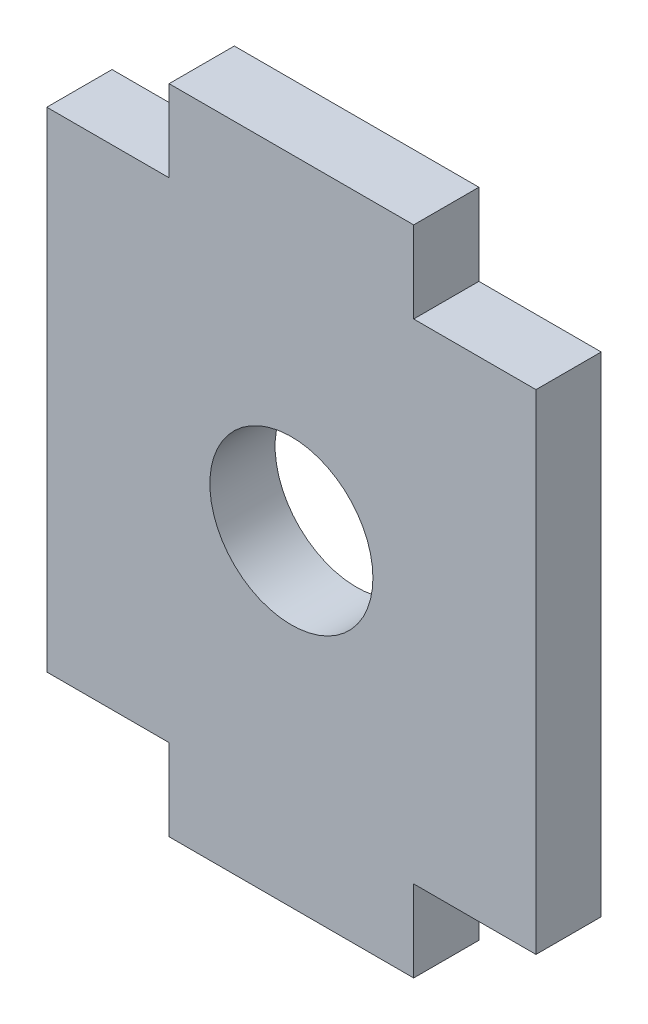
SolidWorks part; units mm, degrees
ref_plane "Front Plane" through (0, 0, 0) normal (0, 0, 1) x (1, 0, 0)
ref_plane "Top Plane" through (0, 0, 0) normal (0, 1, 0) x (1, 0, 0)
ref_plane "Right Plane" through (0, 0, 0) normal (1, 0, 0) x (0, 0, -1)
sketch "Sketch1" plane through (0, 0, 0) normal (0, 0, 1) x (1, 0, 0)
  line L0 (-7.5, 15) -> (-15, 15)
  line L1 (7.5, 20) -> (-7.5, 20)
  line L2 (7.5, 20) -> (7.5, 15)
  line L3 (7.5, -20) -> (-7.5, -20)
  line L4 (-7.5, 20) -> (-7.5, 15)
  line L5 (7.5, 20) -> (-7.5, -20) construction
  line L6 (7.5, -20) -> (-7.5, 20) construction
  line L7 (15, -15) -> (7.5, -15)
  line L8 (15, -15) -> (15, 15)
  line L9 (15, 15) -> (7.5, 15)
  line L10 (-15, -15) -> (-15, 15)
  line L11 (15, -15) -> (-15, 15) construction
  line L12 (15, 15) -> (-15, -15) construction
  line L13 (-7.5, -15) -> (-7.5, -20)
  line L14 (-7.5, -15) -> (-15, -15)
  line L15 (7.5, -15) -> (7.5, -20)
  point P0 (0, 0)
  point P6 (0, 0)
  dimension "D1" = 40
  dimension "D2" = 30
  dimension "D3" = 15
  dimension "D4" = 30
extrude "Boss-Extrude1" add sketch "Sketch1" along normal blind 4
sketch "Sketch2" plane through (0, 0, 4) normal (0, 0, 1) x (1, 0, 0)
  circle A0 centre (0, 0) radius 5
extrude "Cut-Extrude1" cut sketch "Sketch2" against normal blind 4
